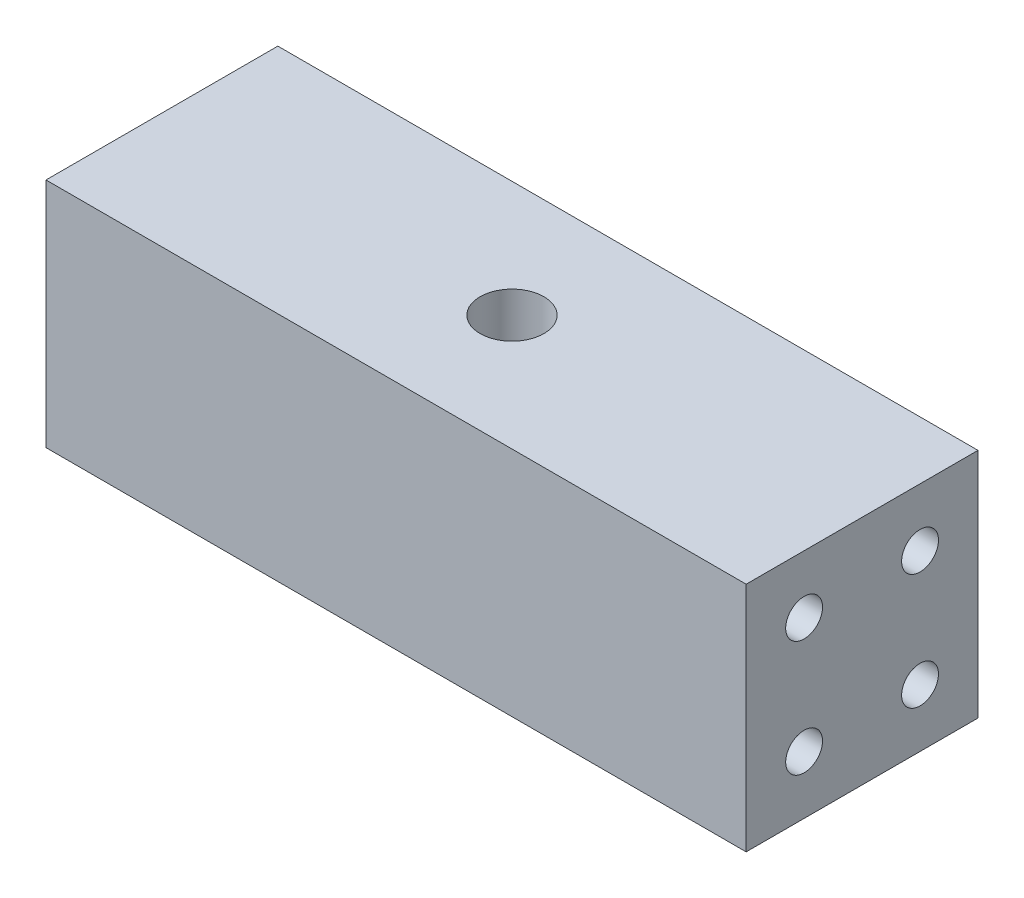
SolidWorks part; units mm, degrees
material "6061-T6 (SS)"
ref_plane "Front Plane" through (0, 0, 0) normal (0, 0, 1) x (1, 0, 0)
ref_plane "Top Plane" through (0, 0, 0) normal (0, 1, 0) x (1, 0, 0)
ref_plane "Right Plane" through (0, 0, 0) normal (1, 0, 0) x (0, 0, -1)
sketch "Sketch1" plane through (0, 0, 0) normal (0, 1, 0) x (1, 0, 0)
  line L1 (0, 0) -> (76.708, 0)
  line L2 (0, 0) -> (0, 25.4)
  line L3 (0, 25.4) -> (76.708, 25.4)
  line L4 (76.708, 0) -> (76.708, 25.4)
  dimension "D1" = 25.4
  dimension "D2" = 76.708
extrude "Boss-Extrude1" add sketch "Sketch1" along normal blind 25.4
hole_wizard "#10-32 Tapped Hole1" positions "Sketch2" profile "Sketch3" tap size "#10-32" standard "ANSI Inch"
sketch "Sketch2" plane through (76.708, 0, 0) normal (1, 0, 0) x (0, 0, -1)
  point P0 (6.35, 19.05)
  point P2 (19.05, 19.05)
  point P4 (19.05, 6.35)
  point P6 (6.35, 6.35)
  dimension "D1" = 6.35
  dimension "D2" = 6.35
  dimension "D3" = 6.35
  dimension "D4" = 6.35
  dimension "D5" = 6.35
  dimension "D6" = 6.35
  dimension "D7" = 6.35
  dimension "D8" = 6.35
sketch "Sketch3" plane through (76.708, 19.05, -6.35) normal (0, 1, 0) x (0, 0, -1)
  line L0 (0, 0) -> (0, 9.8493)
  line L1 (0, 9.8493) -> (2.0193, 8.636)
  line L2 (2.0193, 8.636) -> (2.0193, 0)
  line L5 (2.0193, 0) -> (0, 0)
  line L10 (0, 9.8493) -> (-2.0193, 8.636) construction
  line L11 (0, -6.35) -> (0, 107.95) construction
  dimension "Tap Drill Dia." = 4.0386
  dimension "Tap Drill Depth" = 8.636
  dimension "Drill Angle" = 118
cosmetic thread "Hole Thread1" parameters "D1"=6.35, "D2"=4.826
cosmetic thread "Hole Thread2" parameters "D1"=6.35, "D2"=4.826
cosmetic thread "Hole Thread3" parameters "D1"=6.35, "D2"=4.826
cosmetic thread "Hole Thread4" parameters "D1"=6.35, "D2"=4.826
hole_wizard "#10-32 Tapped Hole2" positions "Sketch4" profile "Sketch5" tap size "#10-32" standard "ANSI Inch"
sketch "Sketch4" plane through (0, 0, 0) normal (-1, 0, 0) x (0, 0, 1)
  point P0 (-19.05, 19.05)
  point P2 (-6.35, 19.05)
  point P4 (-6.35, 6.35)
  point P6 (-19.05, 6.35)
  dimension "D1" = 6.35
  dimension "D2" = 6.35
  dimension "D3" = 6.35
  dimension "D4" = 6.35
  dimension "D5" = 6.35
  dimension "D6" = 6.35
  dimension "D7" = 6.35
  dimension "D8" = 6.35
sketch "Sketch5" plane through (0, 19.05, -19.05) normal (0, 1, 0) x (0, 0, 1)
  line L0 (0, 0) -> (0, 9.8493)
  line L1 (0, 9.8493) -> (2.0193, 8.636)
  line L2 (2.0193, 8.636) -> (2.0193, 0)
  line L5 (2.0193, 0) -> (0, 0)
  line L10 (0, 9.8493) -> (-2.0193, 8.636) construction
  line L11 (0, -6.35) -> (0, 107.95) construction
  dimension "Tap Drill Dia." = 4.0386
  dimension "Tap Drill Depth" = 8.636
  dimension "Drill Angle" = 118
cosmetic thread "Hole Thread5" parameters "D1"=6.35, "D2"=4.826
cosmetic thread "Hole Thread6" parameters "D1"=6.35, "D2"=4.826
cosmetic thread "Hole Thread7" parameters "D1"=6.35, "D2"=4.826
cosmetic thread "Hole Thread8" parameters "D1"=6.35, "D2"=4.826
hole_wizard "Ø6.0mm Dowel Hole1" positions "Sketch7" profile "Sketch9" hole size "Ø6.0" standard "ANSI Metric" end condition through all
sketch "Sketch7" plane through (0, 25.4, 0) normal (0, 1, 0) x (1, 0, 0)
  point P0 (38.354, 12.7)
  dimension "D1" = 12.7
  dimension "D2" = 38.354
sketch "Sketch9" plane through (38.354, 25.4, -12.7) normal (1, 0, 0) x (0, 0, 1)
  line L0 (0, 0) -> (0, 25.4)
  line L1 (0, 25.4) -> (3.5, 25.4)
  line L2 (3.5, 25.4) -> (3.5, 0)
  line L5 (3.5, 0) -> (0, 0)
  line L11 (0, -6.35) -> (0, 107.95) construction
  dimension "Thru Hole Dia." = 7
  dimension "Thru Hole Depth" = 25.4
